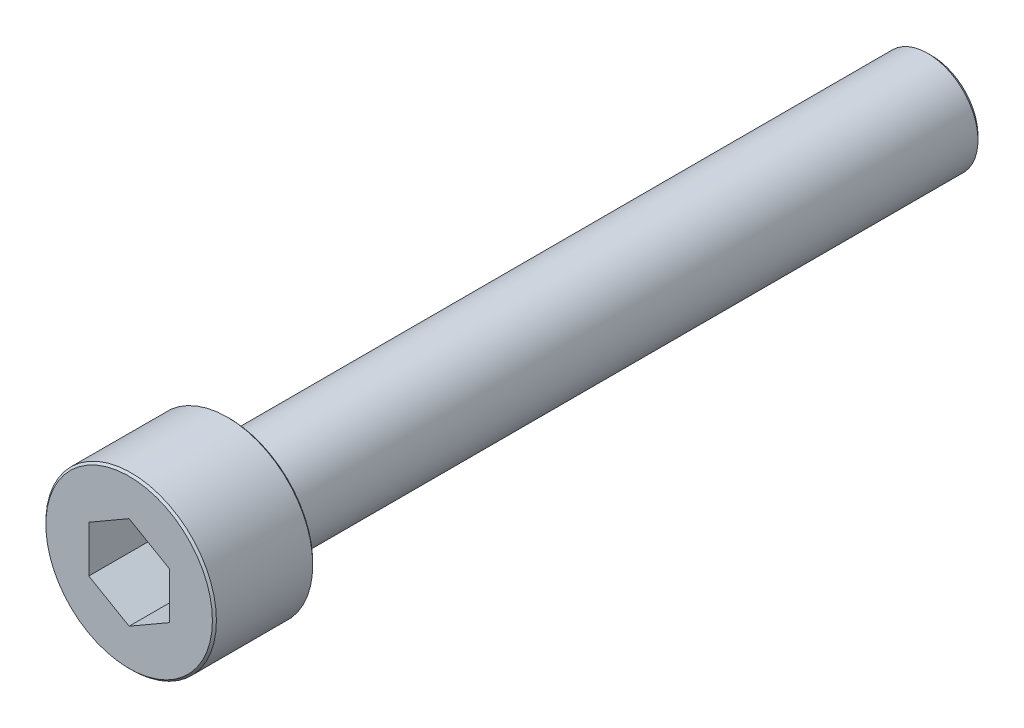
SolidWorks part; units mm, degrees
ref_plane "前视基准面" through (0, 0, 0) normal (0, 0, 1) x (1, 0, 0)
ref_plane "上视基准面" through (0, 0, 0) normal (0, 1, 0) x (1, 0, 0)
ref_plane "右视基准面" through (0, 0, 0) normal (1, 0, 0) x (0, 0, -1)
other "Configuration Table"
sketch "草图1" plane through (0, 0, 0) normal (0, 1, 0) x (1, 0, 0)
  line L0 (4.25, -35) -> (0, -35)
  line L1 (0, -35) -> (0, -40)
  line L2 (0, -40) -> (4.25, -40)
  line L3 (4.25, -40) -> (4.25, -35)
  line L4 (0, -35) -> (0, -40) construction
revolve "旋转1" add sketch "草图1" angle 360 about L4
sketch "草图2" plane through (0, 0, 35) normal (0, 0, -1) x (-1, 0, 0)
  circle A0 centre (0, 0) radius 2.5
extrude "凸台-拉伸1" add sketch "草图2" along normal blind 35
sketch "草图3" plane through (0, 0, 40) normal (0, 0, 1) x (1, 0, 0)
  line L0 (-2.01, -1.1605) -> (0, -2.3209)
  line L1 (0, -2.3209) -> (2.01, -1.1605)
  line L2 (2.01, -1.1605) -> (2.01, 1.1605)
  line L3 (2.01, 1.1605) -> (0, 2.3209)
  line L4 (0, 2.3209) -> (-2.01, 1.1605)
  line L5 (-2.01, 1.1605) -> (-2.01, -1.1605)
extrude "切除-拉伸1" cut sketch "草图3" against normal blind 3.75
chamfer "倒角1" distance 0.1 angle 45 2 edges at (4.25, 0, 35) (4.25, 0, 40)
chamfer "倒角2" distance 0.2001 angle 45.001 1 edges at (-2.5, 0, 0)
